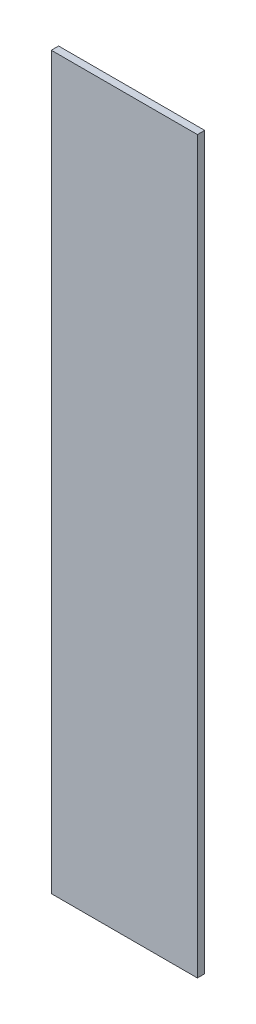
SolidWorks part; units mm, degrees
ref_plane "前视基准面" through (0, 0, 0) normal (0, 0, 1) x (1, 0, 0)
ref_plane "上视基准面" through (0, 0, 0) normal (0, 1, 0) x (1, 0, 0)
ref_plane "右视基准面" through (0, 0, 0) normal (1, 0, 0) x (0, 0, -1)
sketch "草图1" plane through (0, 0, 0) normal (0, 0, 1) x (1, 0, 0)
  line L1 (13.4232, 47.035) -> (33.4232, 47.035)
  line L2 (13.4232, 47.035) -> (13.4232, -52.965)
  line L3 (13.4232, -52.965) -> (33.4232, -52.965)
  line L4 (33.4232, 47.035) -> (33.4232, -52.965)
  dimension "D1" = 100
  dimension "D2" = 20
extrude "凸台-拉伸1" add sketch "草图1" along normal blind 1
